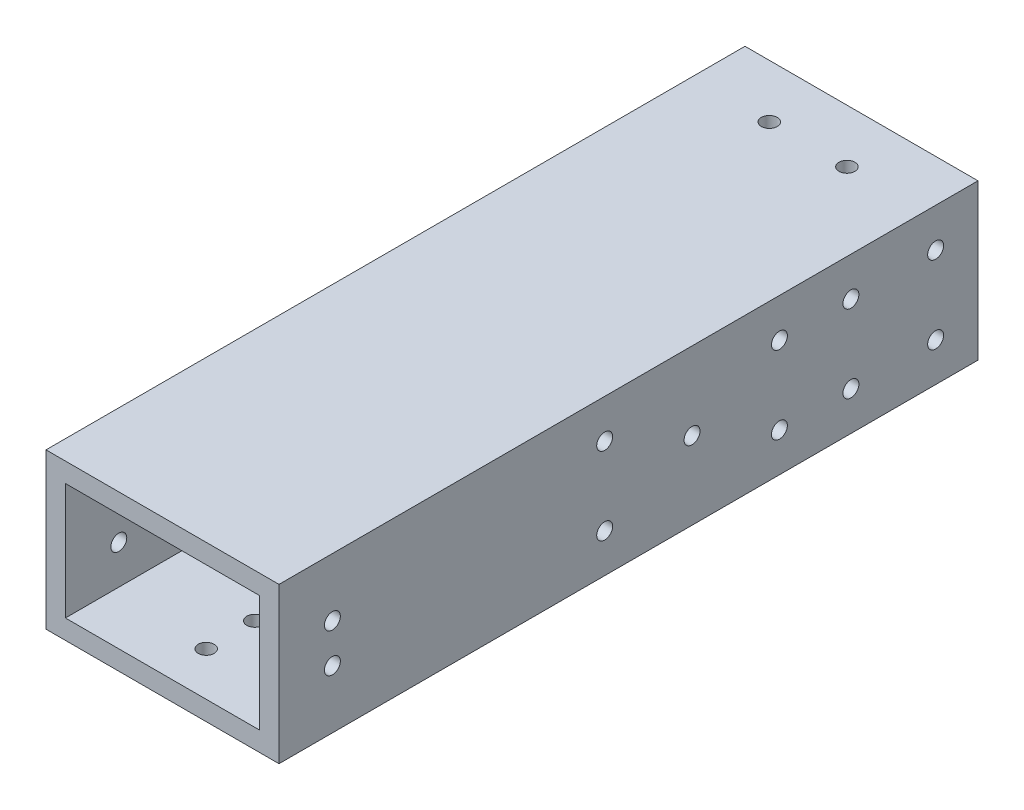
SolidWorks part; units mm, degrees
ref_plane "Front Plane" through (0, 0, 0) normal (0, 0, 1) x (1, 0, 0)
ref_plane "Top Plane" through (0, 0, 0) normal (0, 1, 0) x (1, 0, 0)
ref_plane "Right Plane" through (0, 0, 0) normal (1, 0, 0) x (0, 0, -1)
sketch "Sketch1" plane through (0, 0, 0) normal (0, 0, 1) x (1, 0, 0)
  line L8 (38.1, 737.3561) -> (38.1, 788.1561) construction
  line L12 (-38.1, 788.1561) -> (-38.1, 737.3561) construction
  line L16 (-47.625, 788.1561) -> (-38.1, 788.1561) construction
  line L17 (31.75, 743.7061) -> (-31.75, 743.7061)
  line L18 (38.1, 737.3561) -> (-38.1, 737.3561)
  line L19 (38.1, 737.3561) -> (38.1, 788.1561)
  line L20 (38.1, 788.1561) -> (-38.1, 788.1561)
  line L21 (-38.1, 737.3561) -> (-38.1, 788.1561)
  line L22 (-31.75, 743.7061) -> (-31.75, 781.8061)
  line L23 (31.75, 781.8061) -> (-31.75, 781.8061)
  line L24 (31.75, 743.7061) -> (31.75, 781.8061)
  line L25 (-47.625, 788.1561) -> (-38.1, 788.1561) construction
  dimension "D2" = 50.8
  dimension "D3" = 76.2
  dimension "D1" = 6.35
extrude "Boss-Extrude1" add sketch "Sketch1" against normal blind 76.2 and the other way blind 152.4
sketch "Sketch2" plane through (0, 0, 0) normal (1, 0, 0) x (0, 0, -1)
  line L1 (20.784, 737.7456) -> (20.784, 781.8061) construction
  line L2 (76.2, 737.3561) -> (48.492, 762.7561) construction
  line L3 (20.784, 762.7561) -> (76.2, 762.7561) construction
  line L4 (76.2, 788.1561) -> (-152.4, 788.1561)
  line L5 (76.2, 737.3561) -> (76.2, 788.1561)
  line L6 (-152.4, 737.3561) -> (76.2, 737.3561)
  line L7 (-152.4, 788.1561) -> (-152.4, 737.3561)
  line L8 (76.2, 788.1561) -> (-152.4, 788.1561) construction
  line L9 (76.2, 737.3561) -> (76.2, 788.1561) construction
  line L10 (-152.4, 737.3561) -> (76.2, 737.3561) construction
  line L11 (-152.4, 788.1561) -> (-152.4, 737.3561) construction
  line L12 (48.492, 762.7561) -> (48.492, 737.3561) construction
  line L13 (20.784, 737.7456) -> (20.784, 781.8061) construction
  circle A0 centre (-45.891, 775.4561) radius 3.175 construction
  circle A1 centre (-45.891, 750.0561) radius 3.175 construction
  circle A2 centre (-17.316, 762.7561) radius 3.175 construction
  circle A3 centre (11.259, 775.4561) radius 3.175 construction
  circle A4 centre (11.259, 750.0561) radius 3.175 construction
  circle A5 centre (-45.891, 775.4561) radius 3.175 construction
  circle A6 centre (-45.891, 750.0561) radius 3.175 construction
  circle A7 centre (-17.316, 762.7561) radius 3.175 construction
  circle A8 centre (11.259, 775.4561) radius 3.175 construction
  circle A9 centre (11.259, 750.0561) radius 3.175 construction
  circle A10 centre (62.346, 750.0561) radius 2.6035
  circle A11 centre (34.638, 750.0561) radius 2.6035
  circle A12 centre (34.638, 775.4561) radius 2.6035
  circle A13 centre (62.346, 775.4561) radius 2.6035
  circle A14 centre (11.259, 750.0561) radius 2.6035
  circle A15 centre (11.259, 775.4561) radius 2.6035
  circle A16 centre (-17.316, 762.7561) radius 2.6035
  circle A17 centre (-45.891, 775.4561) radius 2.6035
  circle A18 centre (-45.891, 750.0561) radius 2.6035
  dimension "D2" = 5.207
  dimension "D3" = 5.207
  dimension "D1" = 0
extrude "Cut-Extrude1" cut sketch "Sketch2" against normal through all both and the other way through all
sketch "Sketch3" plane through (38.1, 0, 0) normal (1, 0, 0) x (0, 0, -1)
  circle A0 centre (-134.9375, 769.1061) radius 3.175 construction
  circle A1 centre (-134.9375, 756.4061) radius 3.175 construction
  circle A2 centre (-134.9375, 769.1061) radius 3.175 construction
  circle A3 centre (-134.9375, 756.4061) radius 3.175 construction
  circle A4 centre (-134.9375, 769.1061) radius 2.6035
  circle A5 centre (-134.9375, 756.4061) radius 2.6035
  dimension "D1" = 5.207
extrude "Cut-Extrude2" cut sketch "Sketch3" against normal through all
sketch "Sketch4" plane through (0, 788.1561, 0) normal (0, 1, 0) x (1, 0, 0)
  circle A0 centre (-12.7, 58.7375) radius 3.175 construction
  circle A1 centre (12.7, 58.7375) radius 3.175 construction
  circle A2 centre (-12.7, 58.7375) radius 3.175 construction
  circle A3 centre (12.7, 58.7375) radius 3.175 construction
  circle A4 centre (12.7, 58.7375) radius 2.6035
  circle A5 centre (-12.7, 58.7375) radius 2.6035
  dimension "D1" = 5.207
extrude "Cut-Extrude3" cut sketch "Sketch4" against normal through all
sketch "Sketch5" plane through (0, 737.3561, 0) normal (0, -1, 0) x (1, 0, 0)
  line L0 (-3.302, 120.65) -> (-3.302, 139.7) construction
  line L1 (3.302, 120.65) -> (3.302, 139.7) construction
  line L2 (-3.302, 120.65) -> (-3.302, 139.7) construction
  line L3 (3.302, 120.65) -> (3.302, 139.7) construction
  line L4 (0, 139.7) -> (0, 120.65) construction
  line L5 (-3.302, 130.175) -> (3.302, 130.175) construction
  arc A0 (-3.302, 120.65) -> (3.302, 120.65) centre (0, 120.65) ccw construction
  arc A1 (3.302, 139.7) -> (-3.302, 139.7) centre (0, 139.7) ccw construction
  arc A2 (-3.302, 120.65) -> (3.302, 120.65) centre (0, 120.65) ccw construction
  arc A3 (3.302, 139.7) -> (-3.302, 139.7) centre (0, 139.7) ccw construction
  circle A4 centre (0, 138.1125) radius 2.6035
  circle A5 centre (0, 122.2375) radius 2.6035
  dimension "D1" = 5.207
  dimension "D2" = 1.5875
extrude "Cut-Extrude4" cut sketch "Sketch5" against normal up to next
